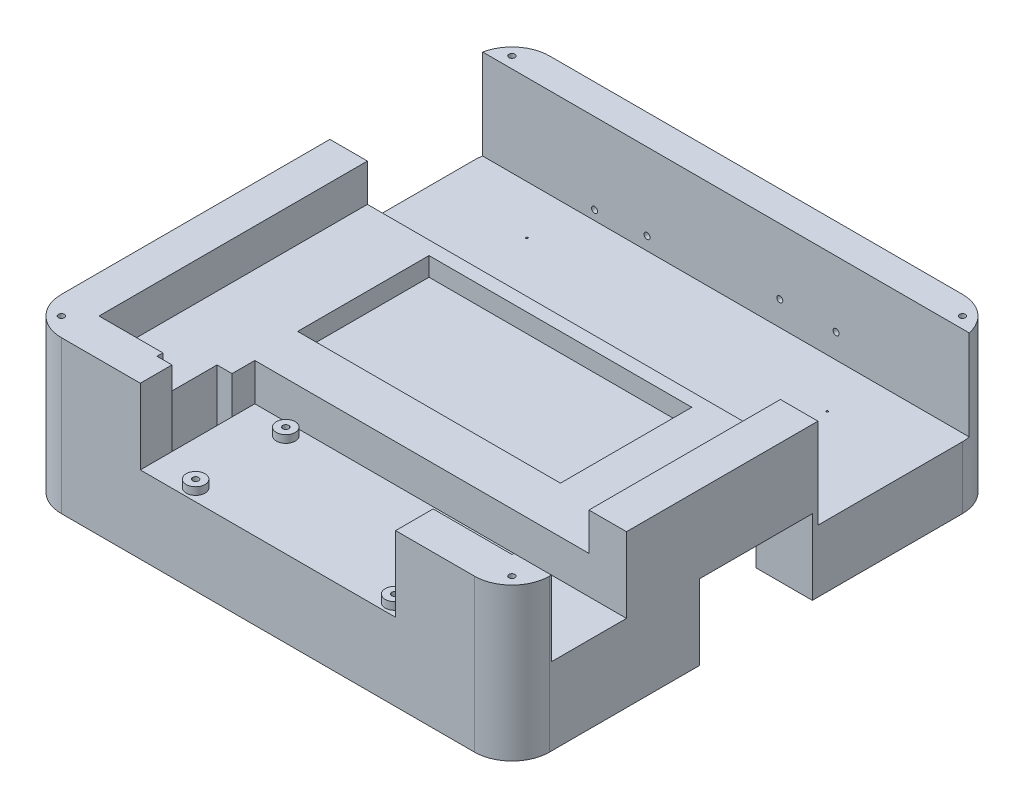
SolidWorks part; units mm, degrees
ref_plane "前视基准面" through (0, 0, 0) normal (0, 0, 1) x (1, 0, 0)
ref_plane "上视基准面" through (0, 0, 0) normal (0, 1, 0) x (1, 0, 0)
ref_plane "右视基准面" through (0, 0, 0) normal (1, 0, 0) x (0, 0, -1)
sketch "草图1" plane through (0, 0, 0) normal (0, 1, 0) x (1, 0, 0)
  line L1 (-65, -65) -> (65, -65)
  line L2 (-65, -65) -> (-65, 65)
  line L3 (-65, 65) -> (65, 65)
  line L4 (65, -65) -> (65, 65)
  line L5 (-65, -65) -> (65, 65) construction
  line L6 (-65, 65) -> (65, -65) construction
  line L7 (-60, -60) -> (60, -60) construction
  line L8 (-60, -60) -> (-60, 60) construction
  line L9 (-60, 60) -> (60, 60) construction
  line L10 (60, -60) -> (60, 60) construction
  line L11 (-60, -60) -> (60, 60) construction
  line L12 (-60, 60) -> (60, -60) construction
  point P1 (0, 0)
  point P6 (0, 0)
  dimension "D1" = 130
  dimension "D2" = 130
  dimension "D3" = 120
  dimension "D4" = 120
extrude "凸台-拉伸1" add sketch "草图1" along normal blind 40.6
sketch "草图2" plane through (0, 40.6, 0) normal (0, 1, 0) x (1, 0, 0)
  line L0 (65, 65) -> (-65, 65) construction
  line L1 (-65, 16.5) -> (65, 16.5)
  line L2 (-65, 16.5) -> (-65, 57)
  line L3 (-65, 57) -> (65, 57)
  line L4 (65, 16.5) -> (65, 57)
  point P0 (0, 0)
  dimension "D1" = 130
  dimension "D2" = 40.5
  dimension "D3" = 8
extrude "切除-拉伸1" cut sketch "草图2" against normal blind 24
sketch "草图3" plane through (0, 0, 0) normal (0, -1, 0) x (1, 0, 0)
  line L0 (-65, 65) -> (65, 65) construction
  line L1 (34, 65) -> (-34, 65)
  line L2 (34, 65) -> (34, 34.5)
  line L3 (34, 34.5) -> (-34, 34.5)
  line L4 (-34, 65) -> (-34, 34.5)
  dimension "D1" = 68
  dimension "D2" = 30.5
  dimension "D3" = 34
sketch "草图7" plane through (0, 0, 0) normal (0, -1, 0) x (1, 0, 0)
  line L0 (65, 65) -> (65, -65) construction
  line L1 (65, -15) -> (49, -15)
  line L2 (65, -15) -> (65, 15)
  line L3 (65, 15) -> (49, 15)
  line L4 (49, -15) -> (49, 15)
  line L6 (0, 0) -> (0, -37.8172) construction
  line L7 (-65, 15) -> (-49, 15)
  line L8 (-65, -15) -> (-65, 15)
  line L9 (-49, -15) -> (-49, 15)
  line L10 (-65, -15) -> (-49, -15)
  dimension "D1" = 16
  dimension "D2" = 30
  dimension "D3" = 15
extrude "切除-拉伸5" cut sketch "草图7" against normal blind 20
sketch "草图9" plane through (-90.6, 40.6, 0) normal (0, -1, 0) x (0, 0, -1)
  line L1 (10.0584, 25.4653) -> (-9.9416, 25.4653)
  line L2 (10.0584, 25.4653) -> (10.0584, 35.4653)
  line L3 (10.0584, 35.4653) -> (-9.9416, 35.4653)
  line L4 (-9.9416, 25.4653) -> (-9.9416, 35.4653)
  line L5 (10.0584, 25.4653) -> (-9.9416, 35.4653) construction
  line L6 (10.0584, 35.4653) -> (-9.9416, 25.4653) construction
  point P0 (0.0584, 30.4653)
  dimension "D1" = 20
  dimension "D2" = 10
sketch "草图10" plane through (0, 0, 0) normal (0, -1, 0) x (1, 0, 0)
  line L0 (65, -65) -> (-65, -65) construction
  line L1 (-41, -50) -> (41, -50)
  line L2 (-46, -45) -> (-46, 19)
  line L3 (-41, 24) -> (41, 24)
  line L4 (46, -45) -> (46, 19)
  arc A0 (41, 24) -> (46, 19) centre (41, 19) cw
  arc A1 (46, -45) -> (41, -50) centre (41, -45) cw
  arc A2 (-41, -50) -> (-46, -45) centre (-41, -45) cw
  arc A3 (-46, 19) -> (-41, 24) centre (-41, 19) cw
  point P9 (46, 24)
  point P14 (-46, -50)
  point P17 (-46, 24)
  dimension "D5" = 5
  dimension "D1" = 92
  dimension "D2" = 74
  dimension "D3" = 46
  dimension "D4" = 15
extrude "切除-拉伸8" cut sketch "草图10" against normal blind 10
sketch "草图12" plane through (0, 0, 0) normal (0, -1, 0) x (1, 0, 0)
  line L1 (-60, -60) -> (60, -60) construction
  line L2 (-60, -60) -> (-60, 60) construction
  line L3 (-60, 60) -> (60, 60) construction
  line L4 (60, -60) -> (60, 60) construction
  line L5 (-60, -60) -> (60, 60) construction
  line L6 (-60, 60) -> (60, -60) construction
  point P0 (0, 0)
  dimension "D1" = 120
  dimension "D2" = 120
hole_wizard "M2 螺纹孔的螺纹孔钻头1" positions "草图14" profile "草图13" hole size "M2" standard "GB"
sketch "草图14" plane through (0, 0, 0) normal (0, -1, 0) x (-1, 0, 0)
  point P0 (60, -60)
  point P3 (-60, -60)
  point P6 (60, 60)
  point P9 (-60, 60)
sketch "草图13" plane through (-60, 0, 60) normal (1, 0, 0) x (0, 0, -1)
  line L0 (0, 0) -> (0, 8.4807)
  line L1 (0, 8.4807) -> (0.8, 8)
  line L2 (0.8, 8) -> (0.8, 0)
  line L5 (0.8, 0) -> (0, 0)
  line L10 (0, 8.4807) -> (-0.8, 8) construction
  line L11 (0, -6.35) -> (0, 107.95) construction
  dimension "孔直径" = 1.6
  dimension "孔深度" = 8
  dimension "导头角度" = 118
sketch "草图15" plane through (0, 0, 0) normal (0, -1, 0) x (1, 0, 0)
  line L1 (-50, -50) -> (50, -50)
  line L2 (-50, -50) -> (-50, 50)
  line L3 (-50, 50) -> (50, 50)
  line L4 (50, -50) -> (50, 50)
  line L5 (-50, -50) -> (50, 50) construction
  line L6 (-50, 50) -> (50, -50) construction
  point P0 (0, 0)
  dimension "D1" = 100
  dimension "D2" = 100
extrude "切除-拉伸9" cut sketch "草图15" against normal blind 5
fillet "圆角1" radius 10 4 edges at (65, 20.3, 65) (-65, 20.3, 65) (-65, 20.3, -65) (65, 20.3, -65)
hole_wizard "M2 螺纹孔的螺纹孔钻头3" positions "草图22" profile "草图21" hole size "M2" standard "GB"
sketch "草图22" plane through (0, 40.6, 0) normal (0, 1, 0) x (1, 0, 0)
  point P0 (-60, 60)
  point P3 (60, 60)
  point P6 (60, -60)
  point P9 (-60, -60)
sketch "草图21" plane through (-60, 40.6, -60) normal (1, 0, 0) x (0, 0, 1)
  line L0 (0, 0) -> (0, 8.4807)
  line L1 (0, 8.4807) -> (0.8, 8)
  line L2 (0.8, 8) -> (0.8, 0)
  line L5 (0.8, 0) -> (0, 0)
  line L10 (0, 8.4807) -> (-0.8, 8) construction
  line L11 (0, -6.35) -> (0, 107.95) construction
  dimension "孔直径" = 1.6
  dimension "孔深度" = 8
  dimension "导头角度" = 118
sketch "草图24" plane through (0, 40.6, 0) normal (0, 1, 0) x (1, 0, 0)
  line L0 (34, -65) -> (-34, -65) construction
  line L1 (34, -65) -> (34, -34.5) construction
  line L2 (34, -34.5) -> (-34, -34.5) construction
  line L3 (-34, -65) -> (-34, -34.5) construction
  line L4 (34, -65) -> (-34, -65)
  line L5 (34, -65) -> (34, -34.5)
  line L6 (34, -34.5) -> (-34, -34.5)
  line L7 (-34, -65) -> (-34, -34.5)
extrude "切除-拉伸10" cut sketch "草图24" against normal blind 20
sketch "草图25" plane through (0, 40.6, 0) normal (0, 1, 0) x (1, 0, 0)
  line L6 (-34, -34.5) -> (-34, -65) construction
  line L7 (-34, -40.5596) -> (-38, -40.5596)
  line L8 (-34, -40.5596) -> (-34, -56.5596)
  line L9 (-34, -56.5596) -> (-38, -56.5596)
  line L10 (-38, -40.5596) -> (-38, -56.5596)
  line L11 (-34, -48.5596) -> (-25.7071, -48.5596) construction
  dimension "D4" = 16
  dimension "D5" = 4
extrude "切除-拉伸11" cut sketch "草图25" against normal blind 25
sketch "草图26" plane through (0, 40.6, 0) normal (0, 1, 0) x (1, 0, 0)
  line L1 (65, -55) -> (65, 16.5) construction
  line L2 (34, -34.5) -> (65, -34.5)
  line L3 (34, -34.5) -> (34, -54.5)
  line L4 (34, -54.5) -> (65, -54.5)
  line L5 (65, -34.5) -> (65, -54.5)
  dimension "D1" = 20
extrude "切除-拉伸12" cut sketch "草图26" against normal blind 20
sketch "草图27" plane through (0, 20.6, 0) normal (0, 1, 0) x (1, 0, 0)
  line L0 (34, -65) -> (-34, -65) construction
  line L1 (34, -65) -> (34, -54.5) construction
  circle A0 centre (30.5, -61.75) radius 2.5
  circle A2 centre (-22.51, -61.75) radius 2.5
  circle A3 centre (-22.51, -37.74) radius 2.5
  dimension "D1" = 5
  dimension "D6" = 5
  dimension "D8" = 5
  dimension "D2" = 3.25
  dimension "D3" = 3.5
  dimension "D7" = 53.01
  dimension "D9" = 24.01
extrude "凸台-拉伸2" add sketch "草图27" along normal blind 2
sketch "草图28" plane through (0, 40.6, 0) normal (0, 1, 0) x (1, 0, 0)
  line L1 (-34.9934, 12.8991) -> (35.0066, 12.8991)
  line L2 (-34.9934, 12.8991) -> (-34.9934, -22.1009)
  line L3 (-34.9934, -22.1009) -> (35.0066, -22.1009)
  line L4 (35.0066, 12.8991) -> (35.0066, -22.1009)
  line L5 (-34.9934, 12.8991) -> (35.0066, -22.1009) construction
  line L6 (-34.9934, -22.1009) -> (35.0066, 12.8991) construction
  point P0 (0.0066, -4.6009)
  dimension "D1" = 35
  dimension "D2" = 70
extrude "切除-拉伸13" cut sketch "草图28" against normal blind 15
sketch "草图29" plane through (0, 40.6, 0) normal (0, 1, 0) x (1, 0, 0)
  line L1 (-55, 55) -> (55, 55)
  line L2 (-55, 55) -> (-55, -55)
  line L3 (-55, -55) -> (55, -55)
  line L4 (55, 55) -> (55, -55)
  line L5 (-55, 55) -> (55, -55) construction
  line L6 (-55, -55) -> (55, 55) construction
  point P0 (0, 0)
  dimension "D1" = 110
  dimension "D2" = 110
extrude "切除-拉伸14" cut sketch "草图29" against normal blind 10
sketch "草图30" plane through (0, 10, 0) normal (0, -1, 0) x (1, 0, 0)
  line L0 (46, -45) -> (46, 19) construction
  line L1 (41, 24) -> (-41, 24) construction
  line L2 (-41, -50) -> (41, -50) construction
  line L3 (40, 18) -> (40, -44) construction
  line L4 (40, -13) -> (-44.3897, -13) construction
  line L5 (0, 24) -> (0, -47.06) construction
  circle A0 centre (40, 18) radius 2.5
  circle A1 centre (40, -44) radius 2.5
  circle A2 centre (-40, -44) radius 2.5
  circle A3 centre (-40, 18) radius 2.5
  dimension "D1" = 5
  dimension "D4" = 5
  dimension "D2" = 6
  dimension "D3" = 6
  dimension "D5" = 6
extrude "凸台-拉伸4" add sketch "草图30" along normal blind 2
sketch "草图31" plane through (0, 0, -65) normal (0, 0, -1) x (-1, 0, 0)
  line L0 (65, 16.6) -> (65, 40.6) construction
  line L1 (-64.798, 16.6) -> (64.798, 16.6) construction
  line L2 (-64.798, 16.6) -> (64.798, 16.6) construction
  circle A0 centre (35, 19.1) radius 1
  circle A1 centre (21.0332, 20.0639) radius 1
  circle A2 centre (-14.3338, 23.1341) radius 1
  circle A3 centre (-29.3336, 23.0538) radius 1
  dimension "D1" = 2
  dimension "D4" = 2
  dimension "D6" = 2
  dimension "D8" = 2
  dimension "D2" = 30
  dimension "D3" = 2.5
  dimension "D5" = 14
  dimension "D7" = 35.5
  dimension "D9" = 15
hole_wizard "M2 螺纹孔的螺纹孔钻头4" positions "草图33" profile "草图32" hole size "M2" standard "GB"
sketch "草图33" plane through (0, 0, -65) normal (0, 0, -1) x (-1, 0, 0)
  point P0 (-29.3336, 23.0538)
  point P3 (-14.3338, 23.1341)
  point P6 (21.0332, 20.0639)
  point P9 (35, 19.1)
sketch "草图32" plane through (29.3336, 23.0538, -65) normal (1, 0, 0) x (0, 1, 0)
  line L0 (0, 0) -> (0, 8.4807)
  line L1 (0, 8.4807) -> (0.8, 8)
  line L2 (0.8, 8) -> (0.8, 0)
  line L5 (0.8, 0) -> (0, 0)
  line L10 (0, 8.4807) -> (-0.8, 8) construction
  line L11 (0, -6.35) -> (0, 107.95) construction
  dimension "孔直径" = 1.6
  dimension "孔深度" = 8
  dimension "导头角度" = 118
hole_wizard "M3 螺纹孔的螺纹孔钻头1" positions "草图37" profile "草图36" hole size "M3" standard "GB"
sketch "草图37" plane through (0, 8, 0) normal (0, -1, 0) x (-1, 0, 0)
  point P0 (40, -18)
  point P3 (-40, -18)
  point P6 (40, 44)
  point P9 (-40, 44)
sketch "草图36" plane through (-40, 8, 18) normal (1, 0, 0) x (0, 0, -1)
  line L0 (0, 0) -> (0, 8.7511)
  line L1 (0, 8.7511) -> (1.25, 8)
  line L2 (1.25, 8) -> (1.25, 0)
  line L5 (1.25, 0) -> (0, 0)
  line L10 (0, 8.7511) -> (-1.25, 8) construction
  line L11 (0, -6.35) -> (0, 107.95) construction
  dimension "孔直径" = 2.5
  dimension "孔深度" = 8
  dimension "导头角度" = 118
hole_wizard "M2 螺纹孔的螺纹孔钻头7" positions "草图40" profile "草图39" hole size "M2" standard "GB"
sketch "草图40" plane through (0, 22.6, 0) normal (0, 1, 0) x (1, 0, 0)
  point P0 (-22.51, -37.74)
  point P3 (-22.51, -61.75)
  point P6 (30.5, -61.75)
sketch "草图39" plane through (-22.51, 22.6, 37.74) normal (1, 0, 0) x (0, 0, 1)
  line L0 (0, 0) -> (0, 8.4807)
  line L1 (0, 8.4807) -> (0.8, 8)
  line L2 (0.8, 8) -> (0.8, 0)
  line L5 (0.8, 0) -> (0, 0)
  line L10 (0, 8.4807) -> (-0.8, 8) construction
  line L11 (0, -6.35) -> (0, 107.95) construction
  dimension "孔直径" = 1.6
  dimension "孔深度" = 8
  dimension "导头角度" = 118
